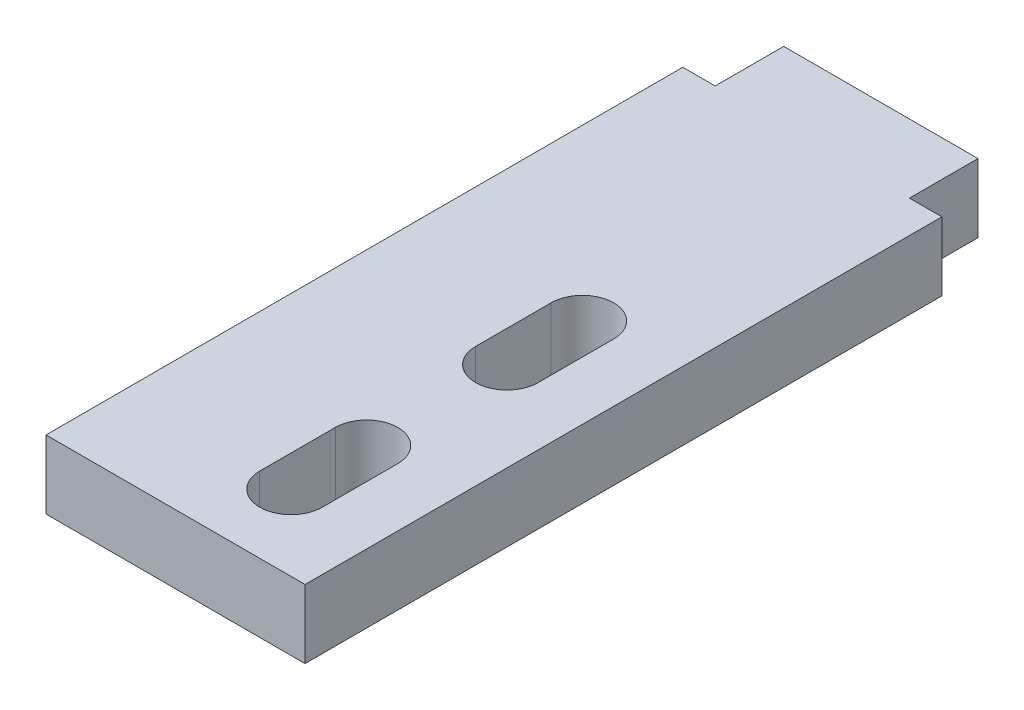
SolidWorks part; units mm, degrees
ref_plane "Front Plane" through (0, 0, 0) normal (0, 0, 1) x (1, 0, 0)
ref_plane "Top Plane" through (0, 0, 0) normal (0, 1, 0) x (1, 0, 0)
ref_plane "Right Plane" through (0, 0, 0) normal (1, 0, 0) x (0, 0, -1)
sketch "Sketch1" plane through (0, 0, 0) normal (0, 1, 0) x (1, 0, 0)
  line L0 (0, -27.5672) -> (0, 22.481) construction
  line L1 (0, 0) -> (52.8966, 0) construction
  line L2 (-32.35, -10.25) -> (-20.35, -10.25)
  line L3 (-20.35, -10.25) -> (-20.35, 19.25)
  line L4 (-20.35, 19.25) -> (-21.85, 19.25)
  line L5 (-32.35, 19.25) -> (-32.35, -10.25)
  line L6 (-24.5, -6.75) -> (-24.5, -3.25) construction
  line L7 (-25.95, -6.75) -> (-25.95, -3.25)
  line L8 (-23.05, -6.75) -> (-23.05, -3.25)
  line L9 (-24.5, 3.25) -> (-24.5, 6.75) construction
  line L10 (-25.95, 3.25) -> (-25.95, 6.75)
  line L11 (-23.05, 3.25) -> (-23.05, 6.75)
  line L12 (-30.85, 19.25) -> (-32.35, 19.25)
  line L14 (-30.85, 19.25) -> (-30.85, 22.425)
  line L15 (-30.85, 22.425) -> (-21.85, 22.425)
  line L16 (-21.85, 19.25) -> (-21.85, 22.425)
  arc A0 (-25.95, 3.25) -> (-23.05, 3.25) centre (-24.5, 3.25) ccw
  arc A1 (-23.05, 6.75) -> (-25.95, 6.75) centre (-24.5, 6.75) ccw
  arc A2 (-25.95, -6.75) -> (-23.05, -6.75) centre (-24.5, -6.75) ccw
  arc A3 (-23.05, -3.25) -> (-25.95, -3.25) centre (-24.5, -3.25) ccw
  point P11 (-24.5, 5)
  point P15 (-24.5, -5)
  dimension "D7" = 1.45
  dimension "D8" = 10
  dimension "D6" = 5
  dimension "D10" = 3.175
  dimension "D1" = 29.5
  dimension "D2" = 12
  dimension "D3" = 20.35
  dimension "D4" = 10.25
  dimension "D5" = 24.5
  dimension "D9" = 3.5
  dimension "D11" = 1.5
  dimension "D12" = 1.5
extrude "Boss-Extrude1" add sketch "Sketch1" along normal blind 3.175
